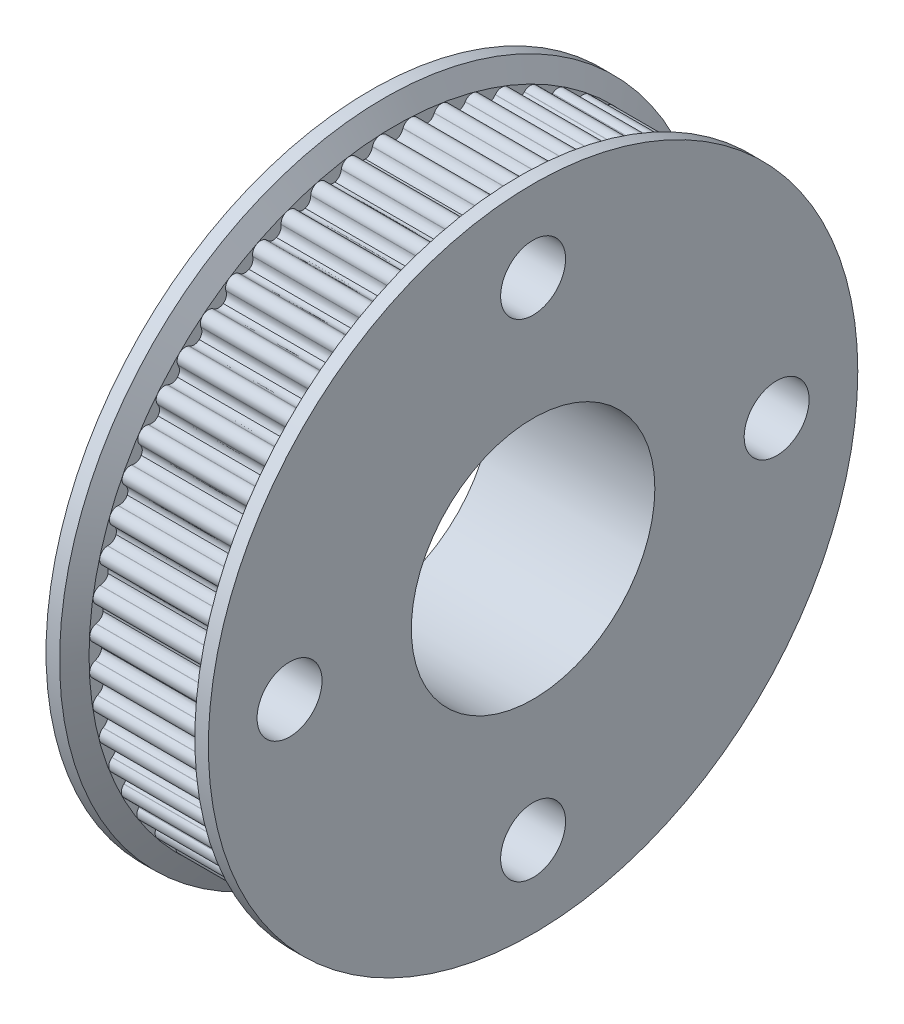
SolidWorks part; units mm, degrees
ref_plane "Front Plane" through (0, 0, 0) normal (0, 0, 1) x (1, 0, 0)
ref_plane "Top Plane" through (0, 0, 0) normal (0, 1, 0) x (1, 0, 0)
ref_plane "Right Plane" through (0, 0, 0) normal (1, 0, 0) x (0, 0, -1)
sketch "Sketch1" plane through (0, 0, 0) normal (0, 1, 0) x (1, 0, 0)
  line L0 (0, 0) -> (-29.5926, 0) construction
  line L1 (0, 7.5) -> (0, 8.9565)
  line L2 (-1.5, 18.85) -> (-8.5, 18.85)
  line L3 (-10, 20) -> (-10, 7.5)
  line L4 (-10, 7.5) -> (0, 7.5)
  line L5 (0, 8.9565) -> (0, 20)
  line L6 (-0.836, 20) -> (-1.5, 18.85)
  line L7 (-10, 4.001) -> (0, 4.001) construction
  line L8 (-5, 18.85) -> (-5, 12.6929) construction
  line L9 (-9.164, 20) -> (-8.5, 18.85)
  line L10 (-10, 20) -> (-8.5, 18.85) construction
  line L11 (-1.5, 18.85) -> (0, 8.9565) construction
  line L12 (-10, 20) -> (-9.164, 20)
  line L13 (-0.836, 20) -> (0, 20)
  point P15 (-5, 4.001)
  dimension "D1" = 10
  dimension "D2" = 7
  dimension "D3" = 37.7
  dimension "D4" = 40
  dimension "D5" = 15
  dimension "D6" = 120
revolve "Revolve1" add sketch "Sketch1" angle 360 about L0
ref_plane "Plane1" through (-1.5, 0, 0) normal (1, 0, 0) x (0, 0, -1)
ref_plane "Plane2" through (-8.5, 0, 0) normal (1, 0, 0) x (0, 0, -1)
sketch "Sketch3" plane through (-1.5, 0, 0) normal (1, 0, 0) x (0, 0, -1)
  line L0 (0.4895, 18.4804) -> (0.4858, 18.4697)
  line L1 (-0.4323, 18.471) -> (-0.436, 18.4817)
  line L2 (-1.3914, 18.4344) -> (-1.394, 18.4234)
  line L3 (-2.3607, 18.3247) -> (-2.3654, 18.3349)
  line L4 (-3.3107, 18.188) -> (-3.3122, 18.1768)
  line L5 (-4.2632, 17.9775) -> (-4.269, 17.9872)
  line L6 (-5.1937, 17.7423) -> (-5.194, 17.731)
  line L7 (-6.119, 17.4334) -> (-6.1258, 17.4424)
  line L8 (-7.0199, 17.1022) -> (-7.019, 17.0909)
  line L9 (-7.9078, 16.6983) -> (-7.9155, 16.7066)
  line L10 (-8.7691, 16.2747) -> (-8.767, 16.2636)
  line L11 (-9.6099, 15.7803) -> (-9.6184, 15.7877)
  line L12 (-10.4222, 15.269) -> (-10.419, 15.2581)
  line L13 (-11.2067, 14.6893) -> (-11.216, 14.6958)
  line L14 (-11.9612, 14.0959) -> (-11.9568, 14.0855)
  line L15 (-12.6808, 13.4374) -> (-12.6907, 13.4429)
  line L16 (-13.3691, 12.7684) -> (-13.3637, 12.7585)
  line L17 (-14.0159, 12.0383) -> (-14.0263, 12.0427)
  line L18 (-14.6305, 11.301) -> (-14.6241, 11.2917)
  line L19 (-15.1975, 10.5073) -> (-15.2083, 10.5106)
  line L20 (-15.7316, 9.7098) -> (-15.7243, 9.7012)
  line L21 (-16.2125, 8.8612) -> (-16.2236, 8.8633)
  line L22 (-16.6604, 8.0122) -> (-16.6522, 8.0044)
  line L23 (-17.05, 7.118) -> (-17.0612, 7.1189)
  line L24 (-17.4066, 6.2268) -> (-17.3977, 6.22)
  line L25 (-17.7006, 5.2968) -> (-17.7119, 5.2965)
  line L26 (-17.9621, 4.3732) -> (-17.9525, 4.3673)
  line L27 (-18.1573, 3.4175) -> (-18.1685, 3.4161)
  line L28 (-18.3209, 2.4717) -> (-18.3107, 2.4669)
  line L29 (-18.415, 1.5008) -> (-18.426, 1.4983)
  line L30 (-18.4789, 0.5431) -> (-18.4682, 0.5394)
  line L31 (-18.471, -0.4323) -> (-18.4817, -0.436)
  line L32 (-18.4344, -1.3914) -> (-18.4234, -1.394)
  line L33 (-18.3247, -2.3607) -> (-18.3349, -2.3654)
  line L34 (-18.188, -3.3107) -> (-18.1768, -3.3122)
  line L35 (-17.9775, -4.2632) -> (-17.9872, -4.269)
  line L36 (-17.7423, -5.1937) -> (-17.731, -5.194)
  line L37 (-17.4334, -6.119) -> (-17.4424, -6.1258)
  line L38 (-17.1022, -7.0199) -> (-17.0909, -7.019)
  line L39 (-16.6983, -7.9078) -> (-16.7066, -7.9155)
  line L40 (-16.2747, -8.7691) -> (-16.2636, -8.767)
  line L41 (-15.7803, -9.6099) -> (-15.7877, -9.6184)
  line L42 (-15.269, -10.4222) -> (-15.2581, -10.419)
  line L43 (-14.6893, -11.2067) -> (-14.6958, -11.216)
  line L44 (-14.0959, -11.9612) -> (-14.0855, -11.9568)
  line L45 (-13.4374, -12.6808) -> (-13.4429, -12.6907)
  line L46 (-12.7684, -13.3691) -> (-12.7585, -13.3637)
  line L47 (-12.0383, -14.0159) -> (-12.0427, -14.0263)
  line L48 (-11.301, -14.6305) -> (-11.2917, -14.6241)
  line L49 (-10.5073, -15.1975) -> (-10.5106, -15.2083)
  line L50 (-9.7098, -15.7316) -> (-9.7012, -15.7243)
  line L51 (-8.8612, -16.2125) -> (-8.8633, -16.2236)
  line L52 (-8.0122, -16.6604) -> (-8.0044, -16.6522)
  line L53 (-7.118, -17.05) -> (-7.1189, -17.0612)
  line L54 (-6.2268, -17.4066) -> (-6.22, -17.3977)
  line L55 (-5.2968, -17.7006) -> (-5.2965, -17.7119)
  line L56 (-4.3732, -17.9621) -> (-4.3673, -17.9525)
  line L57 (-3.4175, -18.1573) -> (-3.4161, -18.1685)
  line L58 (-2.4717, -18.3209) -> (-2.4669, -18.3107)
  line L59 (-1.5008, -18.415) -> (-1.4983, -18.426)
  line L60 (-0.5431, -18.4789) -> (-0.5394, -18.4682)
  line L61 (0.4323, -18.471) -> (0.436, -18.4817)
  line L62 (1.3914, -18.4344) -> (1.394, -18.4234)
  line L63 (2.3607, -18.3247) -> (2.3654, -18.3349)
  line L64 (3.3107, -18.188) -> (3.3122, -18.1768)
  line L65 (4.2632, -17.9775) -> (4.269, -17.9872)
  line L66 (5.1937, -17.7423) -> (5.194, -17.731)
  line L67 (6.119, -17.4334) -> (6.1258, -17.4424)
  line L68 (7.0199, -17.1022) -> (7.019, -17.0909)
  line L69 (7.9078, -16.6983) -> (7.9155, -16.7066)
  line L70 (8.7691, -16.2747) -> (8.767, -16.2636)
  line L71 (9.6099, -15.7803) -> (9.6184, -15.7877)
  line L72 (10.4222, -15.269) -> (10.419, -15.2581)
  line L73 (11.2067, -14.6893) -> (11.216, -14.6958)
  line L74 (11.9612, -14.0959) -> (11.9568, -14.0855)
  line L75 (12.6808, -13.4374) -> (12.6907, -13.4429)
  line L76 (13.3691, -12.7684) -> (13.3637, -12.7585)
  line L77 (14.0159, -12.0383) -> (14.0263, -12.0427)
  line L78 (14.6305, -11.301) -> (14.6241, -11.2917)
  line L79 (15.1975, -10.5073) -> (15.2083, -10.5106)
  line L80 (15.7316, -9.7098) -> (15.7243, -9.7012)
  line L81 (16.2125, -8.8612) -> (16.2236, -8.8633)
  line L82 (16.6604, -8.0122) -> (16.6522, -8.0044)
  line L83 (17.05, -7.118) -> (17.0612, -7.1189)
  line L84 (17.4066, -6.2268) -> (17.3977, -6.22)
  line L85 (17.7006, -5.2968) -> (17.7119, -5.2965)
  line L86 (17.9621, -4.3732) -> (17.9525, -4.3673)
  line L87 (18.1573, -3.4175) -> (18.1685, -3.4161)
  line L88 (18.3209, -2.4717) -> (18.3107, -2.4669)
  line L89 (18.415, -1.5008) -> (18.426, -1.4983)
  line L90 (18.4789, -0.5431) -> (18.4682, -0.5394)
  line L91 (18.471, 0.4323) -> (18.4817, 0.436)
  line L92 (18.4344, 1.3914) -> (18.4234, 1.394)
  line L93 (18.3247, 2.3607) -> (18.3349, 2.3654)
  line L94 (18.188, 3.3107) -> (18.1768, 3.3122)
  line L95 (17.9775, 4.2632) -> (17.9872, 4.269)
  line L96 (17.7423, 5.1937) -> (17.731, 5.194)
  line L97 (17.4334, 6.119) -> (17.4424, 6.1258)
  line L98 (17.1022, 7.0199) -> (17.0909, 7.019)
  line L99 (16.6983, 7.9078) -> (16.7066, 7.9155)
  line L100 (16.2747, 8.7691) -> (16.2636, 8.767)
  line L101 (15.7803, 9.6099) -> (15.7877, 9.6184)
  line L102 (15.269, 10.4222) -> (15.2581, 10.419)
  line L103 (14.6893, 11.2067) -> (14.6958, 11.216)
  line L104 (14.0959, 11.9612) -> (14.0855, 11.9568)
  line L105 (13.4374, 12.6808) -> (13.4429, 12.6907)
  line L106 (12.7684, 13.3691) -> (12.7585, 13.3637)
  line L107 (12.0383, 14.0159) -> (12.0427, 14.0263)
  line L108 (11.301, 14.6305) -> (11.2917, 14.6241)
  line L109 (10.5073, 15.1975) -> (10.5106, 15.2083)
  line L110 (9.7098, 15.7316) -> (9.7012, 15.7243)
  line L111 (8.8141, 16.2382) -> (8.8162, 16.2492)
  line L112 (7.9639, 16.6835) -> (7.9561, 16.6753)
  line L113 (7.0685, 17.0705) -> (7.0694, 17.0818)
  line L114 (6.1763, 17.4246) -> (6.1695, 17.4156)
  line L115 (5.2454, 17.7159) -> (5.2452, 17.7272)
  line L116 (4.3211, 17.9748) -> (4.3153, 17.9651)
  line L117 (3.3649, 18.1671) -> (3.3634, 18.1783)
  line L118 (2.4186, 18.328) -> (2.4138, 18.3178)
  line L119 (1.4475, 18.4193) -> (1.4449, 18.4303)
  arc A0 (-0.436, 18.4817) -> (-1.3914, 18.4344) centre (-0.9065, 18.3126) ccw
  arc A1 (-2.3654, 18.3349) -> (-3.3107, 18.188) centre (-2.8157, 18.1175) ccw
  arc A2 (-4.269, 17.9872) -> (-5.1937, 17.7423) centre (-4.6941, 17.7239) ccw
  arc A3 (-6.1258, 17.4424) -> (-7.0199, 17.1022) centre (-6.521, 17.1362) ccw
  arc A4 (-7.9155, 16.7066) -> (-8.7691, 16.2747) centre (-8.2765, 16.3607) ccw
  arc A5 (-9.6184, 15.7877) -> (-10.4222, 15.269) centre (-9.9413, 15.4059) ccw
  arc A6 (-11.216, 14.6958) -> (-11.9612, 14.0959) centre (-11.4972, 14.2824) ccw
  arc A7 (-12.6907, 13.4429) -> (-13.3691, 12.7684) centre (-12.9272, 13.0023) ccw
  arc A8 (-14.0263, 12.0427) -> (-14.6305, 11.301) centre (-14.2155, 11.5798) ccw
  arc A9 (-15.2083, 10.5106) -> (-15.7316, 9.7098) centre (-15.348, 10.0305) ccw
  arc A10 (-16.2236, 8.8633) -> (-16.6604, 8.0122) centre (-16.3124, 8.3712) ccw
  arc A11 (-17.0612, 7.1189) -> (-17.4066, 6.2268) centre (-17.0981, 6.6203) ccw
  arc A12 (-17.7119, 5.2965) -> (-17.9621, 4.3732) centre (-17.6964, 4.7968) ccw
  arc A13 (-18.1685, 3.4161) -> (-18.3209, 2.4717) centre (-18.1009, 2.9207) ccw
  arc A14 (-18.426, 1.4983) -> (-18.4789, 0.5431) centre (-18.307, 1.0127) ccw
  arc A15 (-18.4817, -0.436) -> (-18.4344, -1.3914) centre (-18.3126, -0.9065) ccw
  arc A16 (-18.3349, -2.3654) -> (-18.188, -3.3107) centre (-18.1175, -2.8157) ccw
  arc A17 (-17.9872, -4.269) -> (-17.7423, -5.1937) centre (-17.7239, -4.6941) ccw
  arc A18 (-17.4424, -6.1258) -> (-17.1022, -7.0199) centre (-17.1362, -6.521) ccw
  arc A19 (-16.7066, -7.9155) -> (-16.2747, -8.7691) centre (-16.3607, -8.2765) ccw
  arc A20 (-15.7877, -9.6184) -> (-15.269, -10.4222) centre (-15.4059, -9.9413) ccw
  arc A21 (-14.6958, -11.216) -> (-14.0959, -11.9612) centre (-14.2824, -11.4972) ccw
  arc A22 (-13.4429, -12.6907) -> (-12.7684, -13.3691) centre (-13.0023, -12.9272) ccw
  arc A23 (-12.0427, -14.0263) -> (-11.301, -14.6305) centre (-11.5798, -14.2155) ccw
  arc A24 (-10.5106, -15.2083) -> (-9.7098, -15.7316) centre (-10.0305, -15.348) ccw
  arc A25 (-8.8633, -16.2236) -> (-8.0122, -16.6604) centre (-8.3712, -16.3124) ccw
  arc A26 (-7.1189, -17.0612) -> (-6.2268, -17.4066) centre (-6.6203, -17.0981) ccw
  arc A27 (-5.2965, -17.7119) -> (-4.3732, -17.9621) centre (-4.7968, -17.6964) ccw
  arc A28 (-3.4161, -18.1685) -> (-2.4717, -18.3209) centre (-2.9207, -18.1009) ccw
  arc A29 (-1.4983, -18.426) -> (-0.5431, -18.4789) centre (-1.0127, -18.307) ccw
  arc A30 (0.436, -18.4817) -> (1.3914, -18.4344) centre (0.9065, -18.3126) ccw
  arc A31 (2.3654, -18.3349) -> (3.3107, -18.188) centre (2.8157, -18.1175) ccw
  arc A32 (4.269, -17.9872) -> (5.1937, -17.7423) centre (4.6941, -17.7239) ccw
  arc A33 (6.1258, -17.4424) -> (7.0199, -17.1022) centre (6.521, -17.1362) ccw
  arc A34 (7.9155, -16.7066) -> (8.7691, -16.2747) centre (8.2765, -16.3607) ccw
  arc A35 (9.6184, -15.7877) -> (10.4222, -15.269) centre (9.9413, -15.4059) ccw
  arc A36 (11.216, -14.6958) -> (11.9612, -14.0959) centre (11.4972, -14.2824) ccw
  arc A37 (12.6907, -13.4429) -> (13.3691, -12.7684) centre (12.9272, -13.0023) ccw
  arc A38 (14.0263, -12.0427) -> (14.6305, -11.301) centre (14.2155, -11.5798) ccw
  arc A39 (15.2083, -10.5106) -> (15.7316, -9.7098) centre (15.348, -10.0305) ccw
  arc A40 (16.2236, -8.8633) -> (16.6604, -8.0122) centre (16.3124, -8.3712) ccw
  arc A41 (17.0612, -7.1189) -> (17.4066, -6.2268) centre (17.0981, -6.6203) ccw
  arc A42 (17.7119, -5.2965) -> (17.9621, -4.3732) centre (17.6964, -4.7968) ccw
  arc A43 (18.1685, -3.4161) -> (18.3209, -2.4717) centre (18.1009, -2.9207) ccw
  arc A44 (18.426, -1.4983) -> (18.4789, -0.5431) centre (18.307, -1.0127) ccw
  arc A45 (18.4817, 0.436) -> (18.4344, 1.3914) centre (18.3126, 0.9065) ccw
  arc A46 (18.3349, 2.3654) -> (18.188, 3.3107) centre (18.1175, 2.8157) ccw
  arc A47 (17.9872, 4.269) -> (17.7423, 5.1937) centre (17.7239, 4.6941) ccw
  arc A48 (17.4424, 6.1258) -> (17.1022, 7.0199) centre (17.1362, 6.521) ccw
  arc A49 (16.7066, 7.9155) -> (16.2747, 8.7691) centre (16.3607, 8.2765) ccw
  arc A50 (15.7877, 9.6184) -> (15.269, 10.4222) centre (15.4059, 9.9413) ccw
  arc A51 (14.6958, 11.216) -> (14.0959, 11.9612) centre (14.2824, 11.4972) ccw
  arc A52 (13.4429, 12.6907) -> (12.7684, 13.3691) centre (13.0023, 12.9272) ccw
  arc A53 (12.0427, 14.0263) -> (11.301, 14.6305) centre (11.5798, 14.2155) ccw
  arc A54 (10.5106, 15.2083) -> (9.7098, 15.7316) centre (10.0305, 15.348) ccw
  arc A55 (8.8162, 16.2492) -> (7.9639, 16.6835) centre (8.3239, 16.3366) ccw
  arc A56 (7.0694, 17.0818) -> (6.1763, 17.4246) centre (6.5707, 17.1172) ccw
  arc A57 (5.2452, 17.7272) -> (4.3211, 17.9748) centre (4.7454, 17.7103) ccw
  arc A58 (3.3634, 18.1783) -> (2.4186, 18.328) centre (2.8682, 18.1093) ccw
  arc A59 (1.4449, 18.4303) -> (0.4895, 18.4804) centre (0.9596, 18.3099) ccw
  circle A61 centre (0, 0) radius 18.335 construction
  spline S0 degree 3 poles (0.4858, 18.4697) (0.4077, 18.2495) (0.2403, 18.0862) (0.0262, 18.0851) knots 0 0 0 0 1 1 1 1
  spline S1 degree 3 poles (0.0262, 18.0851) (-0.1878, 18.0868) (-0.3548, 18.2506) (-0.4323, 18.471) knots 0 0 0 0 1 1 1 1
  spline S2 degree 3 poles (-1.394, 18.4234) (-1.4515, 18.1875) (-1.5982, 18.0156) (-1.8382, 17.9913) knots 0 0 0 0 1 1 1 1
  spline S3 degree 3 poles (-1.8382, 17.9913) (-2.0782, 17.9665) (-2.2567, 18.1053) (-2.3607, 18.3247) knots 0 0 0 0 1 1 1 1
  spline S4 degree 3 poles (-3.3122, 18.1768) (-3.3447, 17.9362) (-3.4726, 17.7498) (-3.7088, 17.7006) knots 0 0 0 0 1 1 1 1
  spline S5 degree 3 poles (-3.7088, 17.7006) (-3.9448, 17.6509) (-4.1368, 17.7702) (-4.2632, 17.9775) knots 0 0 0 0 1 1 1 1
  spline S6 degree 3 poles (-5.194, 17.731) (-5.2012, 17.4883) (-5.309, 17.2896) (-5.5387, 17.216) knots 0 0 0 0 1 1 1 1
  spline S7 degree 3 poles (-5.5387, 17.216) (-5.7682, 17.1418) (-5.9717, 17.2404) (-6.119, 17.4334) knots 0 0 0 0 1 1 1 1
  spline S8 degree 3 poles (-7.019, 17.0909) (-7.0007, 16.8488) (-7.0871, 16.6399) (-7.3079, 16.5427) knots 0 0 0 0 1 1 1 1
  spline S9 degree 3 poles (-7.3079, 16.5427) (-7.5284, 16.445) (-7.7411, 16.5218) (-7.9078, 16.6983) knots 0 0 0 0 1 1 1 1
  spline S10 degree 3 poles (-8.767, 16.2636) (-8.7236, 16.0248) (-8.7877, 15.808) (-8.9971, 15.6882) knots 0 0 0 0 1 1 1 1
  spline S11 degree 3 poles (-8.9971, 15.6882) (-9.2062, 15.568) (-9.4256, 15.6221) (-9.6099, 15.7803) knots 0 0 0 0 1 1 1 1
  spline S12 degree 3 poles (-10.419, 15.2581) (-10.3508, 15.0251) (-10.3919, 14.8028) (-10.5876, 14.6618) knots 0 0 0 0 1 1 1 1
  spline S13 degree 3 poles (-10.5876, 14.6618) (-10.783, 14.5204) (-11.007, 14.5513) (-11.2067, 14.6893) knots 0 0 0 0 1 1 1 1
  spline S14 degree 3 poles (-11.9568, 14.0855) (-11.8647, 13.8608) (-11.8823, 13.6355) (-12.0622, 13.4748) knots 0 0 0 0 1 1 1 1
  spline S15 degree 3 poles (-12.0622, 13.4748) (-12.2418, 13.3137) (-12.4677, 13.321) (-12.6808, 13.4374) knots 0 0 0 0 1 1 1 1
  spline S16 degree 3 poles (-13.3637, 12.7585) (-13.2485, 12.5447) (-13.2425, 12.3187) (-13.4046, 12.1401) knots 0 0 0 0 1 1 1 1
  spline S17 degree 3 poles (-13.4046, 12.1401) (-13.5664, 11.9611) (-13.7918, 11.9448) (-14.0159, 12.0383) knots 0 0 0 0 1 1 1 1
  spline S18 degree 3 poles (-14.6241, 11.2917) (-14.4872, 11.0912) (-14.4576, 10.867) (-14.6002, 10.6725) knots 0 0 0 0 1 1 1 1
  spline S19 degree 3 poles (-14.6002, 10.6725) (-14.7423, 10.4776) (-14.9648, 10.4378) (-15.1975, 10.5073) knots 0 0 0 0 1 1 1 1
  spline S20 degree 3 poles (-15.7243, 9.7012) (-15.5672, 9.5161) (-15.5143, 9.2963) (-15.6358, 9.0879) knots 0 0 0 0 1 1 1 1
  spline S21 degree 3 poles (-15.6358, 9.0879) (-15.7568, 8.8792) (-15.9739, 8.8163) (-16.2125, 8.8612) knots 0 0 0 0 1 1 1 1
  spline S22 degree 3 poles (-16.6522, 8.0044) (-16.4766, 7.8367) (-16.4011, 7.6237) (-16.5001, 7.4037) knots 0 0 0 0 1 1 1 1
  spline S23 degree 3 poles (-16.5001, 7.4037) (-16.5986, 7.1835) (-16.808, 7.0983) (-17.05, 7.118) knots 0 0 0 0 1 1 1 1
  spline S24 degree 3 poles (-17.3977, 6.22) (-17.2055, 6.0715) (-17.1081, 5.8675) (-17.1836, 5.6384) knots 0 0 0 0 1 1 1 1
  spline S25 degree 3 poles (-17.1836, 5.6384) (-17.2585, 5.4091) (-17.4579, 5.3025) (-17.7006, 5.2968) knots 0 0 0 0 1 1 1 1
  spline S26 degree 3 poles (-17.9525, 4.3673) (-17.7459, 4.2398) (-17.6277, 4.0471) (-17.6788, 3.8114) knots 0 0 0 0 1 1 1 1
  spline S27 degree 3 poles (-17.6788, 3.8114) (-17.7294, 3.5755) (-17.9165, 3.4486) (-18.1573, 3.4175) knots 0 0 0 0 1 1 1 1
  spline S28 degree 3 poles (-18.3107, 2.4669) (-18.0919, 2.3616) (-17.9542, 2.1823) (-17.9804, 1.9425) knots 0 0 0 0 1 1 1 1
  spline S29 degree 3 poles (-17.9804, 1.9425) (-18.006, 1.7027) (-18.1788, 1.5569) (-18.415, 1.5008) knots 0 0 0 0 1 1 1 1
  spline S30 degree 3 poles (-18.4682, 0.5394) (-18.2396, 0.4576) (-18.0839, 0.2937) (-18.0849, 0.0524) knots 0 0 0 0 1 1 1 1
  spline S31 degree 3 poles (-18.0849, 0.0524) (-18.0853, -0.1888) (-18.242, -0.3518) (-18.471, -0.4323) knots 0 0 0 0 1 1 1 1
  spline S32 degree 3 poles (-18.4234, -1.394) (-18.1875, -1.4515) (-18.0156, -1.5982) (-17.9913, -1.8382) knots 0 0 0 0 1 1 1 1
  spline S33 degree 3 poles (-17.9913, -1.8382) (-17.9665, -2.0782) (-18.1053, -2.2567) (-18.3247, -2.3607) knots 0 0 0 0 1 1 1 1
  spline S34 degree 3 poles (-18.1768, -3.3122) (-17.9362, -3.3447) (-17.7498, -3.4726) (-17.7006, -3.7088) knots 0 0 0 0 1 1 1 1
  spline S35 degree 3 poles (-17.7006, -3.7088) (-17.6509, -3.9448) (-17.7702, -4.1368) (-17.9775, -4.2632) knots 0 0 0 0 1 1 1 1
  spline S36 degree 3 poles (-17.731, -5.194) (-17.4883, -5.2012) (-17.2896, -5.309) (-17.216, -5.5387) knots 0 0 0 0 1 1 1 1
  spline S37 degree 3 poles (-17.216, -5.5387) (-17.1418, -5.7682) (-17.2404, -5.9717) (-17.4334, -6.119) knots 0 0 0 0 1 1 1 1
  spline S38 degree 3 poles (-17.0909, -7.019) (-16.8488, -7.0007) (-16.6399, -7.0871) (-16.5427, -7.3079) knots 0 0 0 0 1 1 1 1
  spline S39 degree 3 poles (-16.5427, -7.3079) (-16.445, -7.5284) (-16.5218, -7.7411) (-16.6983, -7.9078) knots 0 0 0 0 1 1 1 1
  spline S40 degree 3 poles (-16.2636, -8.767) (-16.0248, -8.7236) (-15.808, -8.7877) (-15.6882, -8.9971) knots 0 0 0 0 1 1 1 1
  spline S41 degree 3 poles (-15.6882, -8.9971) (-15.568, -9.2062) (-15.6221, -9.4256) (-15.7803, -9.6099) knots 0 0 0 0 1 1 1 1
  spline S42 degree 3 poles (-15.2581, -10.419) (-15.0251, -10.3508) (-14.8028, -10.3919) (-14.6618, -10.5876) knots 0 0 0 0 1 1 1 1
  spline S43 degree 3 poles (-14.6618, -10.5876) (-14.5204, -10.783) (-14.5513, -11.007) (-14.6893, -11.2067) knots 0 0 0 0 1 1 1 1
  spline S44 degree 3 poles (-14.0855, -11.9568) (-13.8608, -11.8647) (-13.6355, -11.8823) (-13.4748, -12.0622) knots 0 0 0 0 1 1 1 1
  spline S45 degree 3 poles (-13.4748, -12.0622) (-13.3137, -12.2418) (-13.321, -12.4677) (-13.4374, -12.6808) knots 0 0 0 0 1 1 1 1
  spline S46 degree 3 poles (-12.7585, -13.3637) (-12.5447, -13.2485) (-12.3187, -13.2425) (-12.1401, -13.4046) knots 0 0 0 0 1 1 1 1
  spline S47 degree 3 poles (-12.1401, -13.4046) (-11.9611, -13.5664) (-11.9448, -13.7918) (-12.0383, -14.0159) knots 0 0 0 0 1 1 1 1
  spline S48 degree 3 poles (-11.2917, -14.6241) (-11.0912, -14.4872) (-10.867, -14.4576) (-10.6725, -14.6002) knots 0 0 0 0 1 1 1 1
  spline S49 degree 3 poles (-10.6725, -14.6002) (-10.4776, -14.7423) (-10.4378, -14.9648) (-10.5073, -15.1975) knots 0 0 0 0 1 1 1 1
  spline S50 degree 3 poles (-9.7012, -15.7243) (-9.5161, -15.5672) (-9.2963, -15.5143) (-9.0879, -15.6358) knots 0 0 0 0 1 1 1 1
  spline S51 degree 3 poles (-9.0879, -15.6358) (-8.8792, -15.7568) (-8.8163, -15.9739) (-8.8612, -16.2125) knots 0 0 0 0 1 1 1 1
  spline S52 degree 3 poles (-8.0044, -16.6522) (-7.8367, -16.4766) (-7.6237, -16.4011) (-7.4037, -16.5001) knots 0 0 0 0 1 1 1 1
  spline S53 degree 3 poles (-7.4037, -16.5001) (-7.1835, -16.5986) (-7.0983, -16.808) (-7.118, -17.05) knots 0 0 0 0 1 1 1 1
  spline S54 degree 3 poles (-6.22, -17.3977) (-6.0715, -17.2055) (-5.8675, -17.1081) (-5.6384, -17.1836) knots 0 0 0 0 1 1 1 1
  spline S55 degree 3 poles (-5.6384, -17.1836) (-5.4091, -17.2585) (-5.3025, -17.4579) (-5.2968, -17.7006) knots 0 0 0 0 1 1 1 1
  spline S56 degree 3 poles (-4.3673, -17.9525) (-4.2398, -17.7459) (-4.0471, -17.6277) (-3.8114, -17.6788) knots 0 0 0 0 1 1 1 1
  spline S57 degree 3 poles (-3.8114, -17.6788) (-3.5755, -17.7294) (-3.4486, -17.9165) (-3.4175, -18.1573) knots 0 0 0 0 1 1 1 1
  spline S58 degree 3 poles (-2.4669, -18.3107) (-2.3616, -18.0919) (-2.1823, -17.9542) (-1.9425, -17.9804) knots 0 0 0 0 1 1 1 1
  spline S59 degree 3 poles (-1.9425, -17.9804) (-1.7027, -18.006) (-1.5569, -18.1788) (-1.5008, -18.415) knots 0 0 0 0 1 1 1 1
  spline S60 degree 3 poles (-0.5394, -18.4682) (-0.4576, -18.2396) (-0.2937, -18.0839) (-0.0524, -18.0849) knots 0 0 0 0 1 1 1 1
  spline S61 degree 3 poles (-0.0524, -18.0849) (0.1888, -18.0853) (0.3518, -18.242) (0.4323, -18.471) knots 0 0 0 0 1 1 1 1
  spline S62 degree 3 poles (1.394, -18.4234) (1.4515, -18.1875) (1.5982, -18.0156) (1.8382, -17.9913) knots 0 0 0 0 1 1 1 1
  spline S63 degree 3 poles (1.8382, -17.9913) (2.0782, -17.9665) (2.2567, -18.1053) (2.3607, -18.3247) knots 0 0 0 0 1 1 1 1
  spline S64 degree 3 poles (3.3122, -18.1768) (3.3447, -17.9362) (3.4726, -17.7498) (3.7088, -17.7006) knots 0 0 0 0 1 1 1 1
  spline S65 degree 3 poles (3.7088, -17.7006) (3.9448, -17.6509) (4.1368, -17.7702) (4.2632, -17.9775) knots 0 0 0 0 1 1 1 1
  spline S66 degree 3 poles (5.194, -17.731) (5.2012, -17.4883) (5.309, -17.2896) (5.5387, -17.216) knots 0 0 0 0 1 1 1 1
  spline S67 degree 3 poles (5.5387, -17.216) (5.7682, -17.1418) (5.9717, -17.2404) (6.119, -17.4334) knots 0 0 0 0 1 1 1 1
  spline S68 degree 3 poles (7.019, -17.0909) (7.0007, -16.8488) (7.0871, -16.6399) (7.3079, -16.5427) knots 0 0 0 0 1 1 1 1
  spline S69 degree 3 poles (7.3079, -16.5427) (7.5284, -16.445) (7.7411, -16.5218) (7.9078, -16.6983) knots 0 0 0 0 1 1 1 1
  spline S70 degree 3 poles (8.767, -16.2636) (8.7236, -16.0248) (8.7877, -15.808) (8.9971, -15.6882) knots 0 0 0 0 1 1 1 1
  spline S71 degree 3 poles (8.9971, -15.6882) (9.2062, -15.568) (9.4256, -15.6221) (9.6099, -15.7803) knots 0 0 0 0 1 1 1 1
  spline S72 degree 3 poles (10.419, -15.2581) (10.3508, -15.0251) (10.3919, -14.8028) (10.5876, -14.6618) knots 0 0 0 0 1 1 1 1
  spline S73 degree 3 poles (10.5876, -14.6618) (10.783, -14.5204) (11.007, -14.5513) (11.2067, -14.6893) knots 0 0 0 0 1 1 1 1
  spline S74 degree 3 poles (11.9568, -14.0855) (11.8647, -13.8608) (11.8823, -13.6355) (12.0622, -13.4748) knots 0 0 0 0 1 1 1 1
  spline S75 degree 3 poles (12.0622, -13.4748) (12.2418, -13.3137) (12.4677, -13.321) (12.6808, -13.4374) knots 0 0 0 0 1 1 1 1
  spline S76 degree 3 poles (13.3637, -12.7585) (13.2485, -12.5447) (13.2425, -12.3187) (13.4046, -12.1401) knots 0 0 0 0 1 1 1 1
  spline S77 degree 3 poles (13.4046, -12.1401) (13.5664, -11.9611) (13.7918, -11.9448) (14.0159, -12.0383) knots 0 0 0 0 1 1 1 1
  spline S78 degree 3 poles (14.6241, -11.2917) (14.4872, -11.0912) (14.4576, -10.867) (14.6002, -10.6725) knots 0 0 0 0 1 1 1 1
  spline S79 degree 3 poles (14.6002, -10.6725) (14.7423, -10.4776) (14.9648, -10.4378) (15.1975, -10.5073) knots 0 0 0 0 1 1 1 1
  spline S80 degree 3 poles (15.7243, -9.7012) (15.5672, -9.5161) (15.5143, -9.2963) (15.6358, -9.0879) knots 0 0 0 0 1 1 1 1
  spline S81 degree 3 poles (15.6358, -9.0879) (15.7568, -8.8792) (15.9739, -8.8163) (16.2125, -8.8612) knots 0 0 0 0 1 1 1 1
  spline S82 degree 3 poles (16.6522, -8.0044) (16.4766, -7.8367) (16.4011, -7.6237) (16.5001, -7.4037) knots 0 0 0 0 1 1 1 1
  spline S83 degree 3 poles (16.5001, -7.4037) (16.5986, -7.1835) (16.808, -7.0983) (17.05, -7.118) knots 0 0 0 0 1 1 1 1
  spline S84 degree 3 poles (17.3977, -6.22) (17.2055, -6.0715) (17.1081, -5.8675) (17.1836, -5.6384) knots 0 0 0 0 1 1 1 1
  spline S85 degree 3 poles (17.1836, -5.6384) (17.2585, -5.4091) (17.4579, -5.3025) (17.7006, -5.2968) knots 0 0 0 0 1 1 1 1
  spline S86 degree 3 poles (17.9525, -4.3673) (17.7459, -4.2398) (17.6277, -4.0471) (17.6788, -3.8114) knots 0 0 0 0 1 1 1 1
  spline S87 degree 3 poles (17.6788, -3.8114) (17.7294, -3.5755) (17.9165, -3.4486) (18.1573, -3.4175) knots 0 0 0 0 1 1 1 1
  spline S88 degree 3 poles (18.3107, -2.4669) (18.0919, -2.3616) (17.9542, -2.1823) (17.9804, -1.9425) knots 0 0 0 0 1 1 1 1
  spline S89 degree 3 poles (17.9804, -1.9425) (18.006, -1.7027) (18.1788, -1.5569) (18.415, -1.5008) knots 0 0 0 0 1 1 1 1
  spline S90 degree 3 poles (18.4682, -0.5394) (18.2396, -0.4576) (18.0839, -0.2937) (18.0849, -0.0524) knots 0 0 0 0 1 1 1 1
  spline S91 degree 3 poles (18.0849, -0.0524) (18.0853, 0.1888) (18.242, 0.3518) (18.471, 0.4323) knots 0 0 0 0 1 1 1 1
  spline S92 degree 3 poles (18.4234, 1.394) (18.1875, 1.4515) (18.0156, 1.5982) (17.9913, 1.8382) knots 0 0 0 0 1 1 1 1
  spline S93 degree 3 poles (17.9913, 1.8382) (17.9665, 2.0782) (18.1053, 2.2567) (18.3247, 2.3607) knots 0 0 0 0 1 1 1 1
  spline S94 degree 3 poles (18.1768, 3.3122) (17.9362, 3.3447) (17.7498, 3.4726) (17.7006, 3.7088) knots 0 0 0 0 1 1 1 1
  spline S95 degree 3 poles (17.7006, 3.7088) (17.6509, 3.9448) (17.7702, 4.1368) (17.9775, 4.2632) knots 0 0 0 0 1 1 1 1
  spline S96 degree 3 poles (17.731, 5.194) (17.4883, 5.2012) (17.2896, 5.309) (17.216, 5.5387) knots 0 0 0 0 1 1 1 1
  spline S97 degree 3 poles (17.216, 5.5387) (17.1418, 5.7682) (17.2404, 5.9717) (17.4334, 6.119) knots 0 0 0 0 1 1 1 1
  spline S98 degree 3 poles (17.0909, 7.019) (16.8488, 7.0007) (16.6399, 7.0871) (16.5427, 7.3079) knots 0 0 0 0 1 1 1 1
  spline S99 degree 3 poles (16.5427, 7.3079) (16.445, 7.5284) (16.5218, 7.7411) (16.6983, 7.9078) knots 0 0 0 0 1 1 1 1
  spline S100 degree 3 poles (16.2636, 8.767) (16.0248, 8.7236) (15.808, 8.7877) (15.6882, 8.9971) knots 0 0 0 0 1 1 1 1
  spline S101 degree 3 poles (15.6882, 8.9971) (15.568, 9.2062) (15.6221, 9.4256) (15.7803, 9.6099) knots 0 0 0 0 1 1 1 1
  spline S102 degree 3 poles (15.2581, 10.419) (15.0251, 10.3508) (14.8028, 10.3919) (14.6618, 10.5876) knots 0 0 0 0 1 1 1 1
  spline S103 degree 3 poles (14.6618, 10.5876) (14.5204, 10.783) (14.5513, 11.007) (14.6893, 11.2067) knots 0 0 0 0 1 1 1 1
  spline S104 degree 3 poles (14.0855, 11.9568) (13.8608, 11.8647) (13.6355, 11.8823) (13.4748, 12.0622) knots 0 0 0 0 1 1 1 1
  spline S105 degree 3 poles (13.4748, 12.0622) (13.3137, 12.2418) (13.321, 12.4677) (13.4374, 12.6808) knots 0 0 0 0 1 1 1 1
  spline S106 degree 3 poles (12.7585, 13.3637) (12.5447, 13.2485) (12.3187, 13.2425) (12.1401, 13.4046) knots 0 0 0 0 1 1 1 1
  spline S107 degree 3 poles (12.1401, 13.4046) (11.9611, 13.5664) (11.9448, 13.7918) (12.0383, 14.0159) knots 0 0 0 0 1 1 1 1
  spline S108 degree 3 poles (11.2917, 14.6241) (11.0912, 14.4872) (10.867, 14.4576) (10.6725, 14.6002) knots 0 0 0 0 1 1 1 1
  spline S109 degree 3 poles (10.6725, 14.6002) (10.4776, 14.7423) (10.4378, 14.9648) (10.5073, 15.1975) knots 0 0 0 0 1 1 1 1
  spline S110 degree 3 poles (9.7012, 15.7243) (9.5161, 15.5672) (9.5993, 15.3388) (9.0425, 15.6621) knots 0 0 0 0 1 1 1 1
  spline S111 degree 3 poles (9.0425, 15.6621) (8.8334, 15.7824) (8.77, 15.9994) (8.8141, 16.2382) knots 0 0 0 0 1 1 1 1
  spline S112 degree 3 poles (7.9561, 16.6753) (7.7889, 16.4993) (7.5761, 16.4231) (7.3558, 16.5215) knots 0 0 0 0 1 1 1 1
  spline S113 degree 3 poles (7.3558, 16.5215) (7.1353, 16.6193) (7.0495, 16.8285) (7.0685, 17.0705) knots 0 0 0 0 1 1 1 1
  spline S114 degree 3 poles (6.1695, 17.4156) (6.0216, 17.2231) (5.8179, 17.125) (5.5886, 17.1999) knots 0 0 0 0 1 1 1 1
  spline S115 degree 3 poles (5.5886, 17.1999) (5.3591, 17.2741) (5.2519, 17.4732) (5.2454, 17.7159) knots 0 0 0 0 1 1 1 1
  spline S116 degree 3 poles (4.3153, 17.9651) (4.1883, 17.7581) (3.996, 17.6394) (3.7601, 17.6898) knots 0 0 0 0 1 1 1 1
  spline S117 degree 3 poles (3.7601, 17.6898) (3.5241, 17.7397) (3.3967, 17.9264) (3.3649, 18.1671) knots 0 0 0 0 1 1 1 1
  spline S118 degree 3 poles (2.4138, 18.3178) (2.3091, 18.0986) (2.1303, 17.9604) (1.8904, 17.9859) knots 0 0 0 0 1 1 1 1
  spline S119 degree 3 poles (1.8904, 17.9859) (1.6505, 18.0109) (1.5042, 18.1832) (1.4475, 18.4193) knots 0 0 0 0 1 1 1 1
extrude "Cut-Extrude4" cut sketch "Sketch3" against normal up to surface (7 mm away) flip side to cut up to plane "Plane2"
sketch "Sketch6" plane through (-10, 0, 0) normal (-1, 0, 0) x (0, 0, 1)
  circle A0 centre (0, 15) radius 2
  circle A1 centre (15, 0) radius 2
  circle A2 centre (0, -15) radius 2
  circle A3 centre (-15, 0) radius 2
  point P12 (0, 0)
  dimension "D1" = 4
  dimension "D2" = 15
  dimension "D3" = 4
extrude "Cut-Extrude5" cut sketch "Sketch6" against normal up to surface (10 mm away) up to face at (0, 0, -20)
sketch "Sketch7" plane through (-10, 0, 0) normal (-1, 0, 0) x (0, 0, 1)
  circle A0 centre (0, 15) radius 3
  circle A1 centre (15, 0) radius 3
  circle A2 centre (0, -15) radius 3
  circle A3 centre (-15, 0) radius 3
  point P12 (0, 0)
  dimension "D1" = 6
  dimension "D2" = 4
extrude "Cut-Extrude6" cut sketch "Sketch7" against normal blind 3
